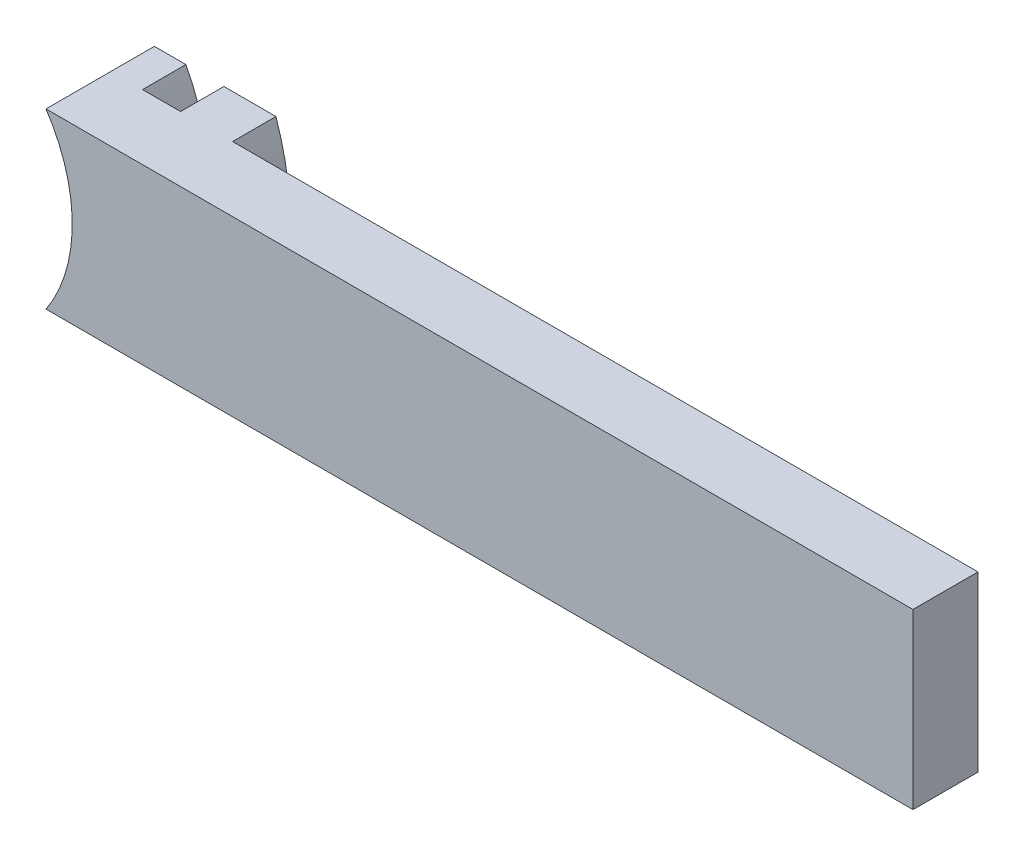
SolidWorks part; units mm, degrees
ref_plane "Front Plane" through (0, 0, 0) normal (0, 0, 1) x (1, 0, 0)
ref_plane "Top Plane" through (0, 0, 0) normal (0, 1, 0) x (1, 0, 0)
ref_plane "Right Plane" through (0, 0, 0) normal (1, 0, 0) x (0, 0, -1)
sketch "Sketch3" plane through (0, 0, 0) normal (0, 0, 1) x (1, 0, 0)
  line L0 (0, 0) -> (36.0555, 0) construction
  line L5 (230, 20) -> (230, -20)
  line L6 (30, 20) -> (230, 20)
  line L7 (30, -20) -> (230, -20)
  arc A1 (30, 20) -> (30, -20) centre (0, 0) cw
  point P15 (0, 0)
  dimension "D4" = 40
  dimension "D1" = 36.0555
  dimension "D2" = 200
  dimension "D3" = 40
extrude "Boss-Extrude1" add sketch "Sketch3" against normal blind 15
sketch "Sketch6" plane through (0, 0, -15) normal (0, 0, -1) x (-1, 0, 0)
  line L2 (-37.2732, 20) -> (-30, 20)
  line L3 (-37.2732, -20) -> (-30, -20)
  line L4 (-46.0439, 20) -> (-58.0439, 20)
  line L5 (-46.0439, -20) -> (-58.0439, -20)
  arc A0 (-30, 20) -> (-30, -20) centre (0, 0) ccw construction
  arc A1 (-30, 20) -> (-30, -20) centre (0, 0) ccw
  arc A2 (-37.2732, -20) -> (-37.2732, 20) centre (0, 0) cw
  arc A3 (-46.0439, -20) -> (-46.0439, 20) centre (0, 0) cw
  arc A4 (-58.0439, 20) -> (-58.0439, -20) centre (0, 0) ccw
  point P25 (0, 0)
  dimension "D1" = 42.3
  dimension "D2" = 50.2
  dimension "D3" = 7.2732
  dimension "D6" = 12
  dimension "D5" = 40
extrude "Boss-Extrude2" add sketch "Sketch6" along normal blind 10
